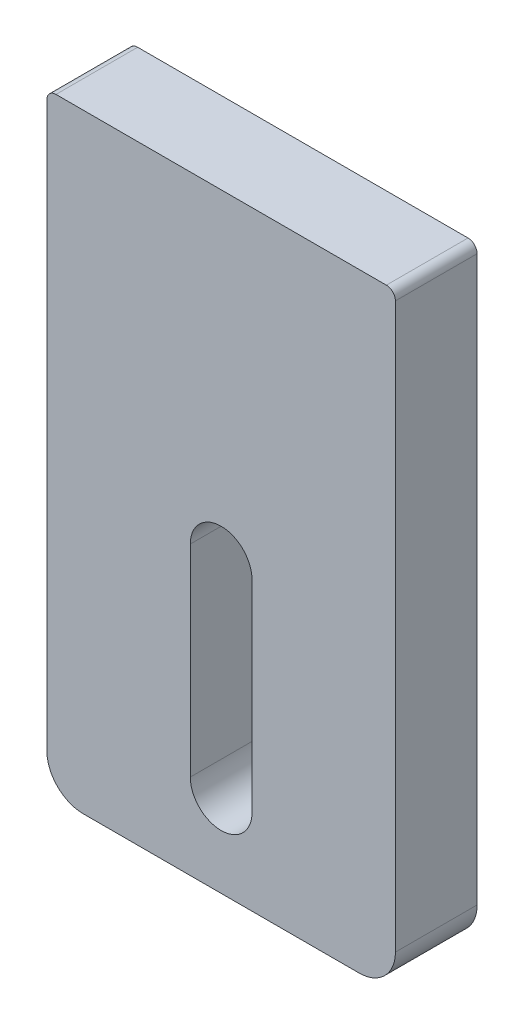
SolidWorks part; units mm, degrees
ref_plane "Front Plane" through (0, 0, 0) normal (0, 0, 1) x (1, 0, 0)
ref_plane "Top Plane" through (0, 0, 0) normal (0, 1, 0) x (1, 0, 0)
ref_plane "Right Plane" through (0, 0, 0) normal (1, 0, 0) x (0, 0, -1)
sketch "Sketch1" plane through (0, 0, 0) normal (0, 0, 1) x (1, 0, 0)
  line L0 (0, 0) -> (10, 0) construction
  line L1 (0, 0) -> (0, 10) construction
  line L2 (-10, -39.6559) -> (10, -39.6559) construction
  line L3 (-10, 21) -> (10, 21) construction
  line L4 (10, 21) -> (10, -17.7509) construction
  line L5 (-10, -17.7509) -> (-10, 21) construction
  line L6 (24.9333, -39.6559) -> (-24.9333, -39.6559) construction
  line L7 (-10, 21) -> (10, 21) construction
  line L8 (10, 21) -> (10, -39.6559) construction
  line L9 (-10, -39.6559) -> (-10, 21) construction
  line L11 (0, 21) -> (0, -10) construction
  line L12 (-1.7, -28.867) -> (-1.7, -17.7509)
  line L13 (1.7, -17.7509) -> (1.7, -28.867)
  line L14 (9.6, -33.567) -> (9.6, 0)
  line L15 (9.6, 0) -> (-9.6, 0)
  line L16 (-9.6, 0) -> (-9.6, -33.567)
  line L17 (-9.6, -33.567) -> (9.6, -33.567)
  line L18 (0, -28.867) -> (0, -33.567) construction
  line L19 (0, 0) -> (0, -10) construction
  line L20 (0, -28.867) -> (0, -17.7509) construction
  line L23 (64.0663, 158.7854) -> (53.5926, 145.1357) construction
  line L24 (56.29, 143.0659) -> (66.7637, 156.7156) construction
  line L25 (64.0663, 158.7854) -> (53.5926, 145.1357) construction
  line L26 (56.29, 143.0659) -> (66.7637, 156.7156) construction
  line L27 (19.6318, 222.3985) -> (139.6318, 14.5524) construction
  line L28 (19.6318, 222.3985) -> (139.6318, 14.5524) construction
  circle A0 centre (0, 0) radius 10 construction
  circle A1 centre (0, 0) radius 10 construction
  circle A2 centre (0, -28.867) radius 4.7 construction
  circle A3 centre (14.7, -17.7509) radius 4.7 construction
  arc A4 (1.7, -17.7509) -> (-1.7, -17.7509) centre (0, -17.7509) ccw
  arc A5 (-1.7, -28.867) -> (1.7, -28.867) centre (0, -28.867) ccw
  arc A6 (1.7, -17.7509) -> (-1.7, -17.7509) centre (0, -17.7509) ccw construction
  arc A7 (53.5926, 145.1357) -> (56.29, 143.0659) centre (54.9413, 144.1008) ccw construction
  arc A8 (66.7637, 156.7156) -> (64.0663, 158.7854) centre (65.415, 157.7505) ccw construction
  arc A9 (53.5926, 145.1357) -> (56.29, 143.0659) centre (54.9413, 144.1008) ccw construction
  arc A10 (66.7637, 156.7156) -> (64.0663, 158.7854) centre (65.415, 157.7505) ccw construction
  circle A11 centre (61.7083, 152.9198) radius 1.7 construction
  circle A12 centre (0, 72.5) radius 103.067 construction
  dimension "D1" = 0.4
  dimension "D3" = 10
extrude "Boss-Extrude1" add sketch "Sketch1" along normal blind 5
fillet "Fillet1" radius 2 2 edges at (-9.6, -33.567, 2.5) (9.6, -33.567, 2.5)
sketch "Sketch2" plane through (0, 0, 0) normal (0, 0, 1) x (1, 0, 0)
  line L0 (9.6, -33.567) -> (9.6, 0) construction
  line L1 (9.6, 0) -> (-9.6, 0) construction
  line L2 (-9.6, 0) -> (-9.6, -33.567) construction
  line L3 (9.6, -10) -> (9.6, 0)
  line L4 (9.6, 0) -> (-9.6, 0)
  line L5 (-9.6, 0) -> (-9.6, -10)
  line L6 (-9.6, -10) -> (9.6, -10)
  circle A0 centre (0, 0) radius 10 construction
extrude "Cut-Extrude1" cut sketch "Sketch2" along normal blind 0.5
fillet "Fillet2" radius 0.5 2 edges at (9.6, 0, 2.75) (-9.6, 0, 2.75)
chamfer "Chamfer1" distance 0.5 angle 45 5 edges at (-9.6, -20.7835, 0) (-9.0142, -32.9812, 0) (0, -33.567, 0) (9.0142, -32.9812, 0) (9.6, -20.7835, 0)
